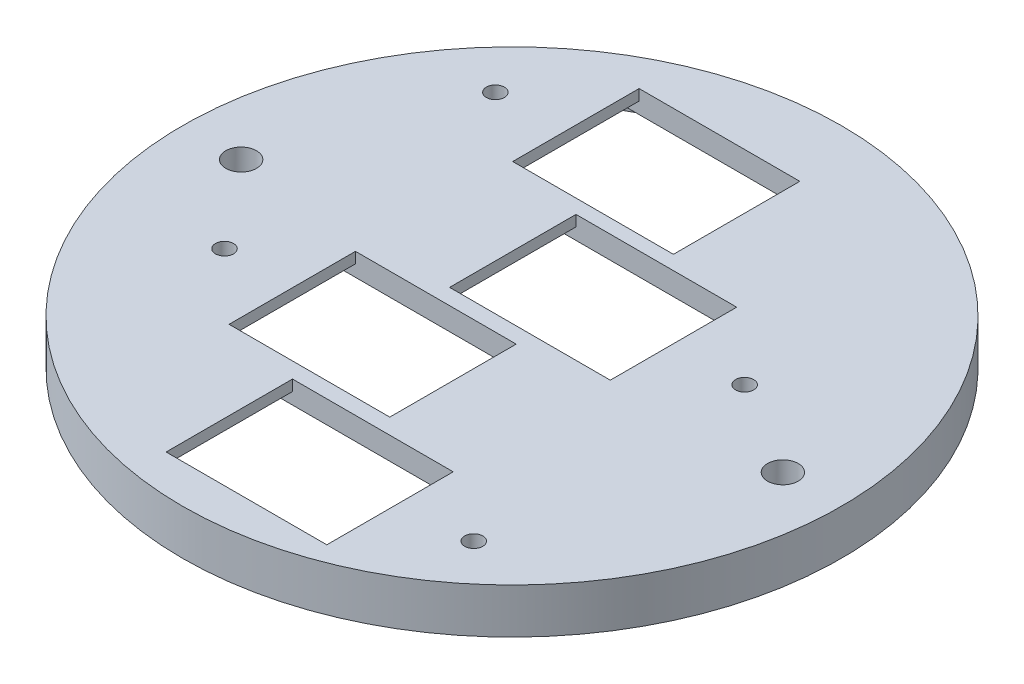
SolidWorks part; units mm, degrees
ref_plane "Front Plane" through (0, 0, 0) normal (0, 0, 1) x (1, 0, 0)
ref_plane "Top Plane" through (0, 0, 0) normal (0, 1, 0) x (1, 0, 0)
ref_plane "Right Plane" through (0, 0, 0) normal (1, 0, 0) x (0, 0, -1)
sketch "Sketch1" plane through (0, 0, 0) normal (0, 1, 0) x (1, 0, 0)
  circle A0 centre (33.3397, -14.8564) radius 36.5
  dimension "D1" = 73
extrude "Boss-Extrude1" add sketch "Sketch1" along normal blind 5
sketch "Sketch2" plane through (0, 5, 0) normal (0, 1, 0) x (1, 0, 0)
  line L1 (25.1357, -33.0625) -> (47.1357, -33.0625)
  line L2 (25.1357, -33.0625) -> (25.1357, -47.0625)
  line L3 (25.1357, -47.0625) -> (47.1357, -47.0625)
  line L4 (47.1357, -33.0625) -> (47.1357, -47.0625)
  line L5 (16.3744, -17.3266) -> (38.3744, -17.3266)
  line L6 (16.3744, -17.3266) -> (16.3744, -31.3266)
  line L7 (16.3744, -31.3266) -> (38.3744, -31.3266)
  line L8 (38.3744, -17.3266) -> (38.3744, -31.3266)
  line L13 (16.4676, 13.994) -> (38.4676, 13.994)
  line L14 (16.4676, 13.994) -> (16.4676, -0.006)
  line L15 (16.4676, -0.006) -> (38.4676, -0.006)
  line L16 (38.4676, 13.994) -> (38.4676, -0.006)
  line L17 (25.0435, -1.5731) -> (47.0435, -1.5731)
  line L18 (25.0435, -1.5731) -> (25.0435, -15.5731)
  line L19 (25.0435, -15.5731) -> (47.0435, -15.5731)
  line L20 (47.0435, -1.5731) -> (47.0435, -15.5731)
  dimension "D1" = 22
  dimension "D2" = 14
  dimension "D5" = 22
  dimension "D6" = 14
  dimension "D8" = 22
  dimension "D9" = 14
  dimension "D13" = 22
  dimension "D14" = 14
extrude "Cut-Extrude1" cut sketch "Sketch2" against normal blind 2.5
sketch "Sketch6" plane through (38.4676, 0, 0) normal (-1, 0, 0) x (0, 0, 1)
  line L0 (0.006, 5) -> (-13.994, 5)
  line L3 (-13.994, 3.8) -> (0.006, 3.8)
  line L4 (0.006, 5) -> (0.006, 3.8)
  line L5 (-13.994, 5) -> (-13.994, 3.8)
  line L6 (51.3564, 5) -> (-21.6436, 5) construction
  line L7 (-13.994, 2.5) -> (-13.994, 5) construction
  dimension "D1" = 14
  dimension "D2" = 1.2
  dimension "D3" = 0
  dimension "D4" = 0
extrude "Boss-Extrude2" add sketch "Sketch6" along normal blind 2.1
sketch "Sketch7" plane through (16.4676, 0, 0) normal (1, 0, 0) x (0, 0, -1)
  line L0 (13.994, 5) -> (-0.006, 5)
  line L3 (-0.006, 3.8) -> (13.994, 3.8)
  line L4 (13.994, 5) -> (13.994, 3.8)
  line L5 (-0.006, 5) -> (-0.006, 3.8)
  line L6 (-15.5731, 5) -> (-1.5731, 5) construction
  line L7 (13.994, 2.5) -> (13.994, 5) construction
  dimension "D1" = 14
  dimension "D2" = 1.2
  dimension "D3" = 0
  dimension "D4" = 0
extrude "Boss-Extrude3" add sketch "Sketch7" along normal blind 2.1
sketch "Sketch8" plane through (25.0435, 0, 0) normal (1, 0, 0) x (0, 0, -1)
  line L0 (-1.5731, 5) -> (-15.5731, 5)
  line L3 (-15.5731, 3.8) -> (-1.5731, 3.8)
  line L4 (-1.5731, 5) -> (-1.5731, 3.8)
  line L5 (-15.5731, 5) -> (-15.5731, 3.8)
  line L6 (-15.5731, 5) -> (-1.5731, 5) construction
  line L7 (-15.5731, 2.5) -> (-15.5731, 5) construction
  dimension "D1" = 14
  dimension "D2" = 1.2
  dimension "D3" = 0
  dimension "D4" = 0
extrude "Boss-Extrude4" add sketch "Sketch8" along normal blind 2.1
sketch "Sketch10" plane through (47.0435, 0, 0) normal (-1, 0, 0) x (0, 0, 1)
  line L0 (15.5731, 5) -> (1.5731, 5)
  line L3 (1.5731, 3.8) -> (15.5731, 3.8)
  line L4 (15.5731, 5) -> (15.5731, 3.8)
  line L5 (1.5731, 5) -> (1.5731, 3.8)
  line L6 (51.3564, 5) -> (-21.6436, 5) construction
  line L7 (15.5731, 2.5) -> (15.5731, 5) construction
  dimension "D1" = 14
  dimension "D2" = 1.2
  dimension "D3" = 0
  dimension "D4" = 0
extrude "Boss-Extrude10" add sketch "Sketch10" along normal blind 2.1 contours L5 L3 L4 L0
sketch "Sketch21" plane through (38.3744, 0, 0) normal (-1, 0, 0) x (0, 0, 1)
  line L0 (51.3564, 5) -> (-21.6436, 5) construction
  line L1 (17.3266, 5) -> (31.3266, 5)
  line L2 (17.3266, 5) -> (17.3266, 3.8)
  line L3 (17.3266, 3.8) -> (31.3266, 3.8)
  line L4 (31.3266, 5) -> (31.3266, 3.8)
  line L5 (17.3266, 2.5) -> (17.3266, 5) construction
  dimension "D1" = 14
  dimension "D2" = 1.2
  dimension "D3" = 0
  dimension "D4" = 0
extrude "Boss-Extrude11" add sketch "Sketch21" along normal blind 2.1
sketch "Sketch13" plane through (16.3744, 0, 0) normal (1, 0, 0) x (0, 0, -1)
  line L0 (-17.3266, 5) -> (-31.3266, 5)
  line L3 (-31.3266, 3.8) -> (-17.3266, 3.8)
  line L4 (-17.3266, 5) -> (-17.3266, 3.8)
  line L5 (-31.3266, 5) -> (-31.3266, 3.8)
  line L6 (21.6436, 5) -> (-51.3564, 5) construction
  line L7 (-17.3266, 2.5) -> (-17.3266, 5) construction
  dimension "D1" = 14
  dimension "D2" = 1.2
  dimension "D3" = 0
  dimension "D4" = 0
extrude "Boss-Extrude7" add sketch "Sketch13" along normal blind 2.1
sketch "Sketch14" plane through (47.1357, 0, 0) normal (-1, 0, 0) x (0, 0, 1)
  line L0 (47.0625, 5) -> (33.0625, 5)
  line L3 (33.0625, 3.8) -> (47.0625, 3.8)
  line L4 (47.0625, 5) -> (47.0625, 3.8)
  line L5 (33.0625, 5) -> (33.0625, 3.8)
  line L6 (17.3266, 5) -> (31.3266, 5) construction
  line L7 (47.0625, 2.5) -> (47.0625, 5) construction
  dimension "D1" = 14
  dimension "D2" = 1.2
  dimension "D3" = 0
  dimension "D4" = 0
extrude "Boss-Extrude8" add sketch "Sketch14" along normal blind 2.1
sketch "Sketch18" plane through (25.1357, 0, 0) normal (1, 0, 0) x (0, 0, -1)
  line L0 (-33.0625, 5) -> (-47.0625, 5)
  line L3 (-47.0625, 3.8) -> (-33.0625, 3.8)
  line L4 (-33.0625, 5) -> (-33.0625, 3.8)
  line L5 (-47.0625, 5) -> (-47.0625, 3.8)
  line L6 (21.6436, 5) -> (-51.3564, 5) construction
  line L7 (-47.0625, 2.5) -> (-47.0625, 5) construction
  dimension "D1" = 14
  dimension "D2" = 1.2
  dimension "D3" = 0
  dimension "D4" = 0
extrude "Boss-Extrude9" add sketch "Sketch18" along normal blind 2.1
sketch "Sketch20" plane through (0, 0, 0) normal (0, -1, 0) x (1, 0, 0)
  circle A0 centre (33.3397, 14.8564) radius 36
  circle A1 centre (33.3397, 14.8564) radius 36.5 construction
  dimension "D1" = 72
  dimension "D2" = 0
extrude "Cut-Extrude3" cut sketch "Sketch20" against normal blind 2.5
sketch "Sketch22" plane through (0, 5, 0) normal (0, 1, 0) x (1, 0, 0)
  circle A0 centre (52.8216, -38.5731) radius 1
  circle A1 centre (10.9679, -24.3266) radius 1
  circle A2 centre (10.9679, 5.6734) radius 1
  circle A3 centre (52.8219, -8.5731) radius 1
  point P6 (33.3397, -14.8564)
  dimension "D1" = 2
  dimension "D2" = 2
  dimension "D3" = 2
  dimension "D4" = 2
  dimension "D5" = 30
  dimension "D6" = 30
  dimension "D7" = 22.3718
  dimension "D8" = 19.4822
  dimension "D9" = 20.5298
  dimension "D10" = 6.2833
extrude "Cut-Extrude4" cut sketch "Sketch22" against normal blind 10
sketch "Sketch24" plane through (0, 5, 0) normal (0, 1, 0) x (1, 0, 0)
  circle A0 centre (63.3397, -14.8564) radius 1.7
  circle A1 centre (3.3397, -14.8564) radius 1.7
  point P4 (33.3397, -14.8564)
  dimension "D1" = 3.4
  dimension "D2" = 3.4
  dimension "D3" = 60
  dimension "D4" = 30
extrude "Cut-Extrude5" cut sketch "Sketch24" against normal through all
